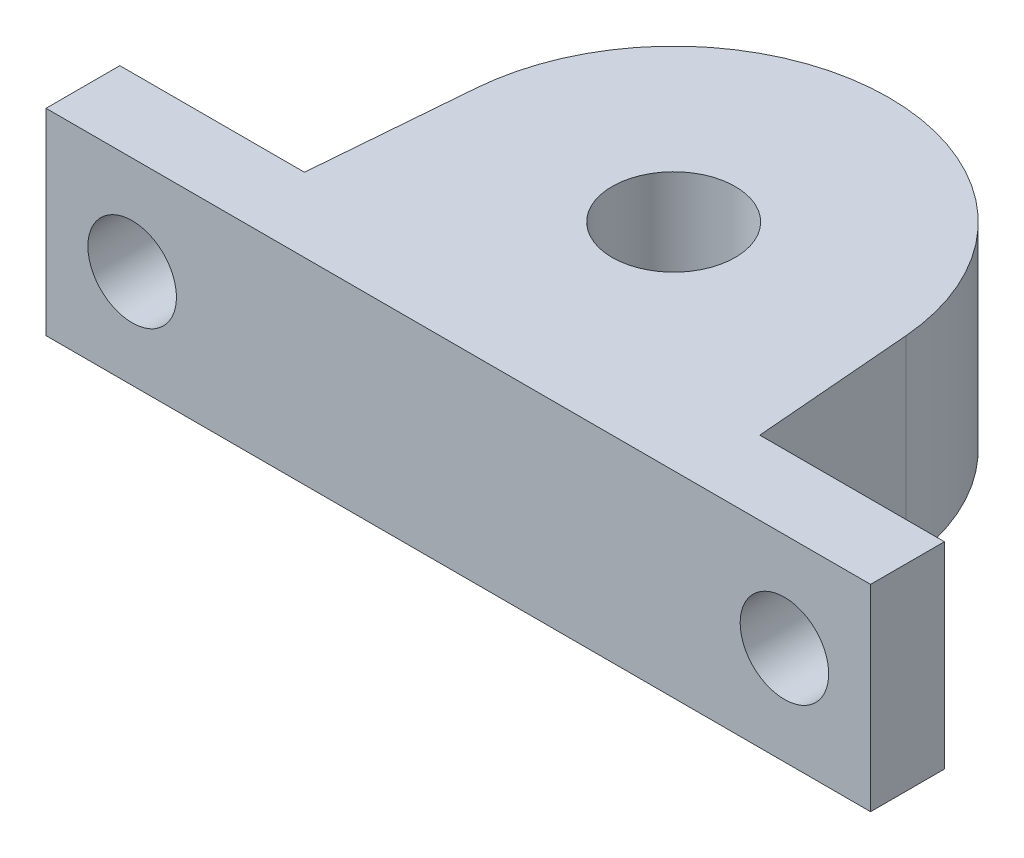
SolidWorks part; units mm, degrees
ref_plane "前视基准面" through (0, 0, 0) normal (0, 0, 1) x (1, 0, 0)
ref_plane "上视基准面" through (0, 0, 0) normal (0, 1, 0) x (1, 0, 0)
ref_plane "右视基准面" through (0, 0, 0) normal (1, 0, 0) x (0, 0, -1)
other "Configuration Table"
sketch "草图1" plane through (0, 0, 0) normal (0, 1, 0) x (1, 0, 0)
  line L0 (-33.5, -17.5) -> (33.5, -17.5)
  line L1 (33.5, -17.5) -> (33.5, -11.5)
  line L2 (33.5, -11.5) -> (18.5, -11.5)
  line L3 (18.5, -11.5) -> (17.4417, 1.4279)
  line L4 (0, -55) -> (0, 55) construction
  line L5 (-33.5, -17.5) -> (-33.5, -11.5)
  line L6 (-33.5, -11.5) -> (-18.5, -11.5)
  line L7 (-18.5, -11.5) -> (-17.4417, 1.4279)
  circle A0 centre (0, 0) radius 17.5
  point P11 (0, -17.5)
  dimension "D1" = 35
  dimension "D2" = 33.5
  dimension "D3" = 6
  dimension "D4" = 15
extrude "凸台-拉伸1" add sketch "草图1" along normal blind 16 contours A0 | A0 L7 L6 L5 L0 | A0 L0 L1 L2 L3
sketch "草图2" plane through (0, 16, 0) normal (0, 1, 0) x (1, 0, 0)
  circle A0 centre (0, 0) radius 5
  dimension "D1" = 10
extrude "切除-拉伸1" cut sketch "草图2" against normal blind 16
sketch "草图3" plane through (0, 0, 11.5) normal (0, 0, -1) x (-1, 0, 0)
  line L0 (-1033.5, 8) -> (48966.5, 8) construction
  line L1 (-33.5, 16) -> (-33.5, 0) construction
  line L2 (0, -1000) -> (0, 49000) construction
  circle A0 centre (-26.5, 8) radius 3.597
  circle A1 centre (26.5, 8) radius 3.597
  point P5 (-33.5, 8)
  dimension "D1" = 26.5
extrude "切除-拉伸2" cut sketch "草图3" against normal blind 16
